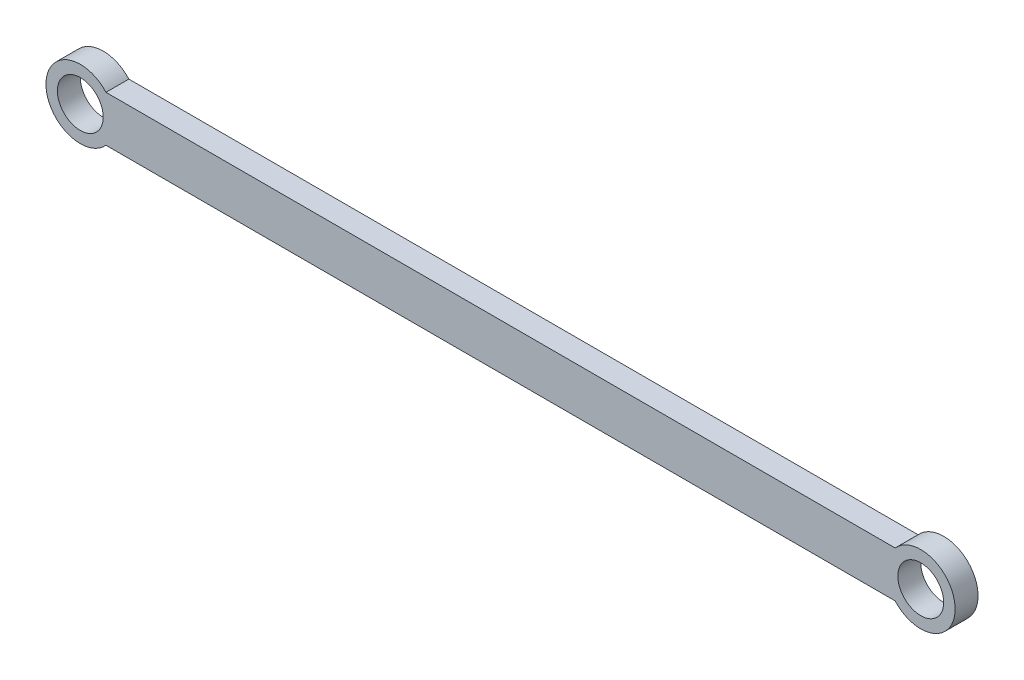
SolidWorks part; units mm, degrees
ref_plane "Front Plane" through (0, 0, 0) normal (0, 0, 1) x (1, 0, 0)
ref_plane "Top Plane" through (0, 0, 0) normal (0, 1, 0) x (1, 0, 0)
ref_plane "Right Plane" through (0, 0, 0) normal (1, 0, 0) x (0, 0, -1)
sketch "Sketch2" plane through (0, 0, 0) normal (0, 0, 1) x (1, 0, 0)
  line L0 (0, 0) -> (-110, 0) construction
  line L1 (-3.3541, -3) -> (-106.6459, -3)
  line L2 (-3.3541, 3) -> (-106.6459, 3)
  arc A2 (-3.3541, -3) -> (-3.3541, 3) centre (0, 0) ccw
  arc A3 (-106.6459, 3) -> (-106.6459, -3) centre (-110, 0) ccw
  circle A4 centre (0, 0) radius 3
  circle A5 centre (-110, 0) radius 3
  point P3 (-55, 0)
  dimension "D3" = 9
  dimension "D1" = 110
  dimension "D2" = 6
extrude "Boss-Extrude1" add sketch "Sketch2" along normal blind 3
